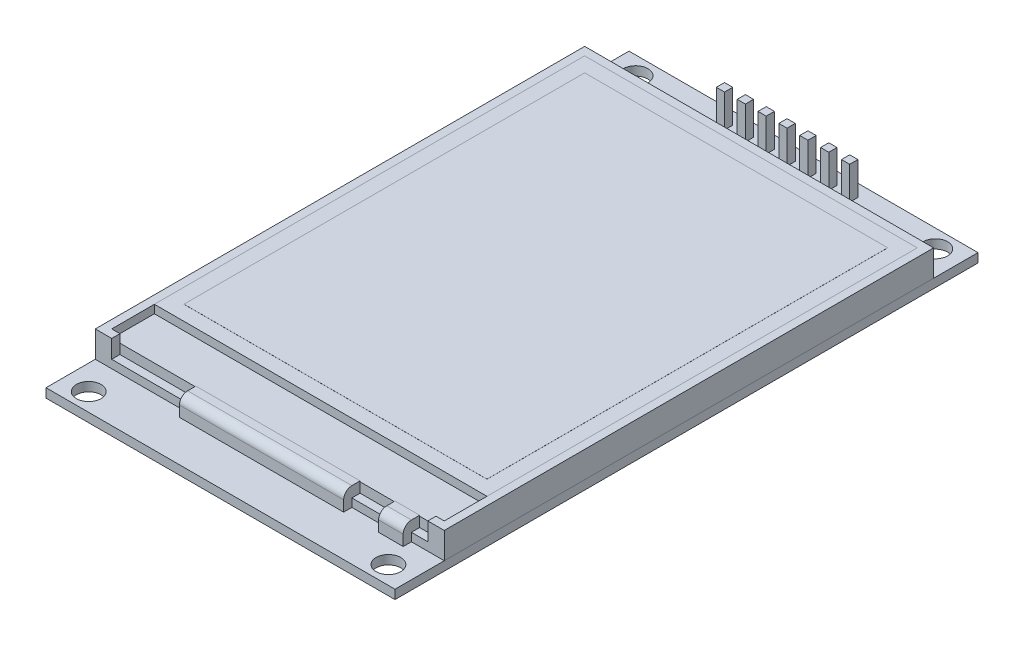
SolidWorks part; units mm, degrees
material "ABS"
ref_plane "Front Plane" through (0, 0, 0) normal (0, 0, 1) x (1, 0, 0)
ref_plane "Top Plane" through (0, 0, 0) normal (0, 1, 0) x (1, 0, 0)
ref_plane "Right Plane" through (0, 0, 0) normal (1, 0, 0) x (0, 0, -1)
sketch "Sketch1" plane through (0, 0, 0) normal (0, 1, 0) x (1, 0, 0)
  line L1 (-21.25, 35.5) -> (21.25, 35.5)
  line L2 (-21.25, 35.5) -> (-21.25, -35.5)
  line L3 (-21.25, -35.5) -> (21.25, -35.5)
  line L4 (21.25, 35.5) -> (21.25, -35.5)
  line L5 (0, -35.5) -> (0, 35.5) construction
  line L6 (-21.25, 0) -> (21.25, 0) construction
  point P0 (0, 0)
  dimension "D1" = 42.5
  dimension "D2" = 71
extrude "Boss-Extrude1" add sketch "Sketch1" along normal blind 1.1
sketch "Sketch7" plane through (0, 1.1, 0) normal (0, 1, 0) x (1, 0, 0)
  line L0 (-21.25, 35.5) -> (21.25, 35.5) construction
  line L1 (-21.25, 35.5) -> (-21.25, -35.5) construction
  circle A0 centre (-18.25, 33.3) radius 1.5
  dimension "D1" = 3
  dimension "D2" = 2.2
  dimension "D3" = 3
extrude "Cut-Extrude2" cut sketch "Sketch7" against normal through all
mirror "Mirror1" about plane through (0, 0, 0) normal (0, 0, 1) of "Cut-Extrude2" second plane through (0, 0, 0) second plane normal (1, 0, 0)
sketch "Sketch8" plane through (0, 1.1, 0) normal (0, 1, 0) x (1, 0, 0)
  line L0 (0, -10.821) -> (0, 10.821) construction
  line L1 (-0.5, 34) -> (0.5, 34)
  line L2 (-0.5, 34) -> (-0.5, 33)
  line L3 (-0.5, 33) -> (0.5, 33)
  line L4 (0.5, 34) -> (0.5, 33)
  line L5 (0, 33) -> (0, 34) construction
  line L6 (-0.5, 33.5) -> (0.5, 33.5) construction
  line L7 (-21.25, 35.5) -> (21.25, 35.5) construction
  point P0 (0, 33.5)
  dimension "D1" = 2
  dimension "D2" = 1
extrude "Boss-Extrude5" add sketch "Sketch8" along normal blind 4 and the other way blind 8
pattern_linear "LPattern1" count 4 spacing 2.54 along (1, 0, 0) count 4 spacing 2.54 along (-1, 0, 0) of "Boss-Extrude5"
sketch "Sketch10" plane through (0, 0, 0) normal (0, -1, 0) x (1, 0, 0)
  line L0 (-21.25, -35.5) -> (-21.25, 35.5) construction
  line L1 (-12.75, -24.5) -> (-3.85, -24.5)
  line L2 (-12.75, -24.5) -> (-12.75, -6.5)
  line L3 (-12.75, -6.5) -> (-3.85, -6.5)
  line L4 (-3.85, -24.5) -> (-3.85, -6.5)
  line L5 (-21.25, -35.5) -> (21.25, -35.5) construction
  dimension "D1" = 8.5
  dimension "D2" = 11
  dimension "D3" = 18
  dimension "D4" = 8.9
extrude "PCB components" add sketch "Sketch10" along normal blind 1.8 separate body
sketch "Sketch2" plane through (0, 1.1, 0) normal (0, 1, 0) x (1, 0, 0)
  line L1 (-21.25, 30.1) -> (21.25, 30.1)
  line L2 (-21.25, 30.1) -> (-21.25, -29.5)
  line L3 (-21.25, -29.5) -> (21.25, -29.5)
  line L4 (21.25, 30.1) -> (21.25, -29.5)
  line L6 (-21.25, 35.5) -> (-21.25, -35.5) construction
  line L7 (21.25, 35.5) -> (21.25, -35.5) construction
  line L8 (-21.25, 35.5) -> (21.25, 35.5) construction
  line L9 (-21.25, -35.5) -> (21.25, -35.5) construction
  line L10 (-21.25, 0.3) -> (21.25, 0.3) construction
  point P4 (0, 0.3)
  dimension "D1" = 5.4
  dimension "D2" = 6
extrude "Boss-Extrude2" add sketch "Sketch2" along normal blind 3.2 separate body
sketch "Sketch3" plane through (0, 4.3, 0) normal (0, 1, 0) x (1, 0, 0)
  line L1 (-20.25, 29.1) -> (20.25, 29.1)
  line L2 (-20.25, 29.1) -> (-20.25, -28.5)
  line L3 (-20.25, -28.5) -> (20.25, -28.5)
  line L4 (20.25, 29.1) -> (20.25, -28.5)
  line L5 (0, -10.821) -> (0, 10.821) construction
  line L6 (-21.25, 30.1) -> (21.25, 30.1) construction
  line L7 (-21.25, 35.5) -> (-21.25, -35.5) construction
  line L9 (-21.25, 0.3) -> (21.25, 0.3) construction
  point P8 (0, 29.1)
  point P12 (-20.25, 0.3)
  dimension "D1" = 1
  dimension "D2" = 1
extrude "Cut-Extrude1" cut sketch "Sketch3" against normal through all
sketch "Sketch12" plane through (0, 0, 29.5) normal (0, 0, 1) x (1, 0, 0)
  line L0 (0, -10.821) -> (0, 10.821) construction
  line L1 (-19.25, 4.3) -> (19.25, 4.3)
  line L2 (-19.25, 4.3) -> (-19.25, 2.1)
  line L3 (-19.25, 2.1) -> (19.25, 2.1)
  line L4 (19.25, 4.3) -> (19.25, 2.1)
  line L5 (-21.25, 4.3) -> (21.25, 4.3) construction
  line L6 (-21.25, 1.1) -> (21.25, 1.1) construction
  point P4 (0, 4.3)
  dimension "D1" = 2
  dimension "D2" = 1
extrude "Cut-Extrude4" cut sketch "Sketch12" against normal up to surface (1 mm away) up to face at (0, 2.7, 28.5)
sketch "Sketch5" plane through (0, 1.1, 0) normal (0, 1, 0) x (1, 0, 0)
  line L4 (20.25, 29.1) -> (-20.25, 29.1)
  line L5 (20.25, -28.5) -> (20.25, 29.1)
  line L6 (-20.25, -28.5) -> (20.25, -28.5)
  line L7 (-20.25, 29.1) -> (-20.25, -28.5)
  line L8 (20.25, 29.1) -> (-20.25, 29.1)
  line L9 (20.25, -28.5) -> (20.25, 29.1)
  line L10 (-20.25, -28.5) -> (20.25, -28.5)
  line L11 (-20.25, 29.1) -> (-20.25, -28.5)
  dimension "D1" = 0
extrude "Boss-Extrude3" add sketch "Sketch5" along normal up to surface (3.2 mm away) separate body up to face at (0, 4.3, 9.4667)
sketch "Sketch9" plane through (0, 4.3, 0) normal (0, 1, 0) x (1, 0, 0)
  line L0 (20.25, 29.1) -> (20.25, -28.5) construction
  line L1 (-20.25, -28.5) -> (20.25, -28.5)
  line L2 (-20.25, -28.5) -> (-20.25, -23.3)
  line L3 (-20.25, -23.3) -> (20.25, -23.3)
  line L4 (20.25, -28.5) -> (20.25, -23.3)
  line L5 (-21.25, -29.5) -> (21.25, -29.5) construction
  dimension "D1" = 6.2
extrude "Cut-Extrude3" cut sketch "Sketch9" against normal blind 1
sketch "Sketch6" plane through (0, 4.3, 0) normal (0, 1, 0) x (1, 0, 0)
  line L0 (0, -10.821) -> (0, 10.821) construction
  line L1 (-18.45, 27.3) -> (18.45, 27.3)
  line L2 (-18.45, 27.3) -> (-18.45, -21.5)
  line L3 (-18.45, -21.5) -> (18.45, -21.5)
  line L4 (18.45, 27.3) -> (18.45, -21.5)
  line L5 (21.25, 35.5) -> (-21.25, 35.5) construction
  line L6 (-20.25, 29.1) -> (20.25, 29.1) construction
  line L7 (-20.25, 29.1) -> (-20.25, -28.5) construction
  line L12 (20.25, 29.1) -> (-20.25, 29.1) construction
  line L13 (-20.25, 29.1) -> (-20.25, -28.5) construction
  line L14 (-21.25, 35.5) -> (-21.25, -35.5) construction
  line L15 (-20.25, -23.3) -> (20.25, -23.3) construction
  line L16 (20.25, -23.3) -> (-20.25, -23.3) construction
  line L17 (-21.25, -35.5) -> (21.25, -35.5) construction
  point P4 (0, 27.3)
  dimension "D1" = 1.8
  dimension "D2" = 1.8
  dimension "D3" = 1.8
  dimension "D4" = 12.2
  dimension "D7" = 6.4
  dimension "D8" = 1
extrude "Boss-Extrude4" add sketch "Sketch6" along normal blind 0.01
sketch "Sketch11" plane through (0, 1.1, 0) normal (0, 1, 0) x (1, 0, 0)
  line L0 (0, -10.821) -> (0, 10.821) construction
  line L1 (-10, -30.5) -> (10, -30.5)
  line L2 (-10, -30.5) -> (-10, -28.5)
  line L3 (-10, -28.5) -> (10, -28.5)
  line L4 (10, -30.5) -> (10, -28.5)
  line L5 (-20.25, -28.5) -> (20.25, -28.5) construction
  line L6 (-21.25, -29.5) -> (21.25, -29.5) construction
  line L7 (21.25, 35.5) -> (21.25, -35.5) construction
  line L8 (14.25, -28.5) -> (17.25, -28.5)
  line L9 (14.25, -28.5) -> (14.25, -30.5)
  line L10 (14.25, -30.5) -> (17.25, -30.5)
  line L11 (17.25, -28.5) -> (17.25, -30.5)
  point P4 (0, -28.5)
  dimension "D1" = 1
  dimension "D2" = 20
  dimension "D3" = 3
  dimension "D4" = 4
extrude "Boss-Extrude7" add sketch "Sketch11" along normal offset from surface (2.3 mm away) 0.1 separate body up to face at (0, 3.3, 25.9) offset beyond the face yes
fillet "Fillet1" radius 1 1 edges at (0, 3.4, 30.5)
fillet "Fillet2" radius 1 1 edges at (15.75, 3.4, 30.5)
equation "\"D1@Boss-Extrude2\"= 4.3 - 1.1"
